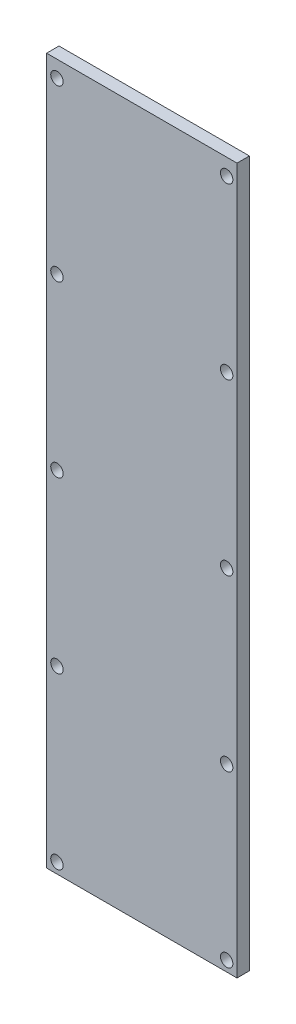
SolidWorks part; units mm, degrees
ref_plane "Přední rovina" through (0, 0, 0) normal (0, 0, 1) x (1, 0, 0)
ref_plane "Horní rovina" through (0, 0, 0) normal (0, 1, 0) x (1, 0, 0)
ref_plane "Pravá rovina" through (0, 0, 0) normal (1, 0, 0) x (0, 0, -1)
sketch "Skica1" plane through (0, 0, 0) normal (0, 0, 1) x (1, 0, 0)
  line L0 (-17, -13) -> (-17, 157.5) construction
  line L1 (-40, -13) -> (6, -13)
  line L2 (-40, -13) -> (-40, 157.5)
  line L3 (-40, 157.5) -> (6, 157.5)
  line L4 (6, -13) -> (6, 157.5)
  line L5 (-40, 72.25) -> (6, 72.25) construction
  line L6 (-37.5, -10.5) -> (3.5, -10.5) construction
  circle A0 centre (-37.5, -10.5) radius 1.5
  circle A3 centre (3.5, -10.5) radius 1.5
  circle A4 centre (3.5, 30.5) radius 1.5
  circle A5 centre (3.5, 71.5) radius 1.5
  circle A6 centre (3.5, 112.5) radius 1.5
  circle A7 centre (3.5, 153.5) radius 1.5
  circle A8 centre (-37.5, 30.5) radius 1.5
  circle A9 centre (-37.5, 71.5) radius 1.5
  circle A10 centre (-37.5, 112.5) radius 1.5
  circle A11 centre (-37.5, 153.5) radius 1.5
  dimension "D1" = 3
  dimension "D2" = 2
  dimension "D4" = 41
  dimension "D3" = 5
extrude "Přidat vysunutím1" add sketch "Skica1" along normal blind 3
sketch "Skica2" plane through (0, 0, 3) normal (0, 0, 1) x (1, 0, 0)
  line L0 (1, -8) -> (1, 152.5)
  line L1 (6, -13) -> (-40, -13)
  line L2 (6, -13) -> (6, 157.5)
  line L3 (6, 157.5) -> (-40, 157.5)
  line L4 (-40, -13) -> (-40, 157.5)
  line L5 (1, 152.5) -> (-35, 152.5)
  line L6 (-35, -8) -> (-35, 152.5)
  line L7 (1, -8) -> (-35, -8)
  line L8 (0, -7) -> (0, 151.5)
  line L9 (0, 151.5) -> (-34, 151.5)
  line L10 (-34, -7) -> (-34, 151.5)
  line L11 (0, -7) -> (-34, -7)
  dimension "D1" = 5
  dimension "D2" = 1
extrude "Přidat vysunutím2" add sketch "Skica2" against normal blind 6 contours L7 L0 L5 L6 L8 L11 L10 L9
